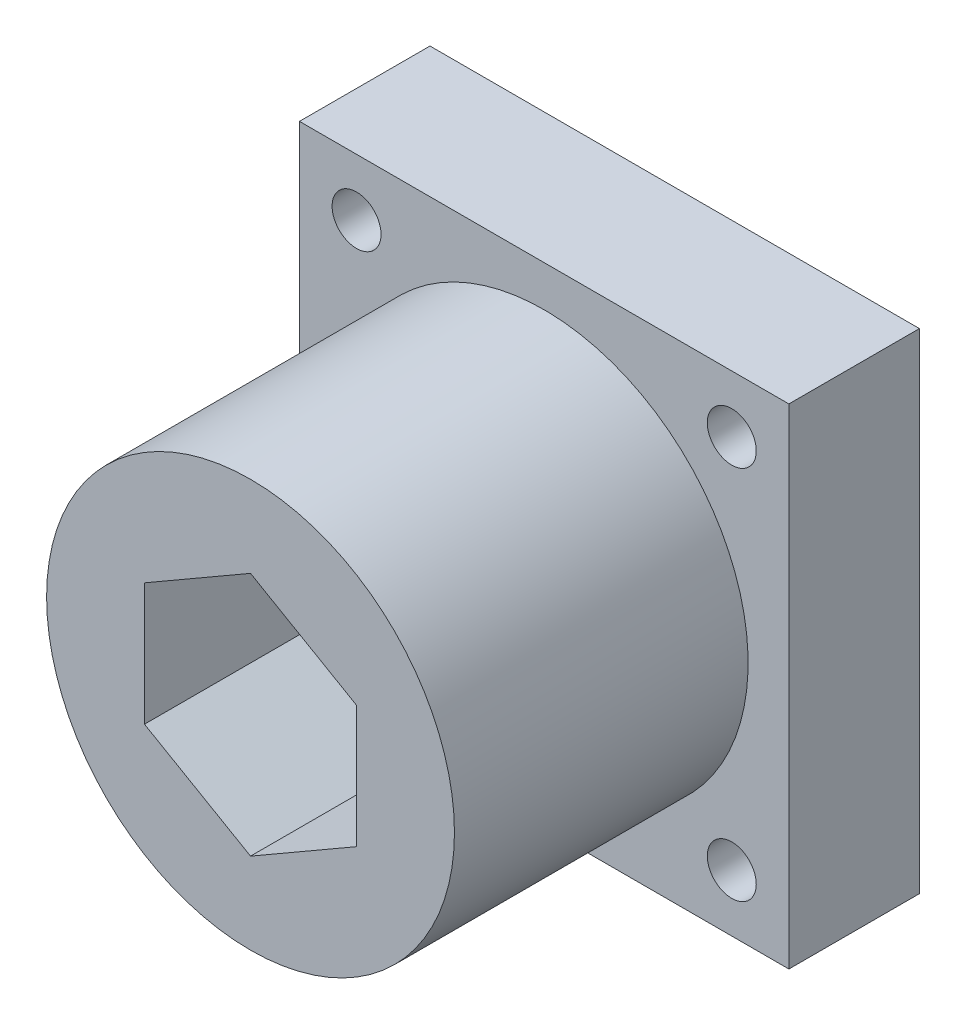
SolidWorks part; units mm, degrees
ref_plane "Ön Düzlem" through (0, 0, 0) normal (0, 0, 1) x (1, 0, 0)
ref_plane "Üst Düzlem" through (0, 0, 0) normal (0, 1, 0) x (1, 0, 0)
ref_plane "Sağ Düzlem" through (0, 0, 0) normal (1, 0, 0) x (0, 0, -1)
sketch "Çizim1" plane through (0, 0, 0) normal (0, 0, 1) x (1, 0, 0)
  line L1 (0, 0) -> (30, 0)
  line L2 (0, 0) -> (0, 30)
  line L3 (0, 30) -> (30, 30)
  line L4 (30, 0) -> (30, 30)
  dimension "D1" = 30
extrude "Yükseklik-Ekstrüzyon1" add sketch "Çizim1" along normal blind 8
sketch "Çizim2" plane through (0, 0, 8) normal (0, 0, 1) x (1, 0, 0)
  line L0 (30, 0) -> (30, 30) construction
  line L1 (0, 0) -> (30, 0) construction
  line L3 (15, 22.5056) -> (8.5, 18.7528)
  line L4 (8.5, 18.7528) -> (8.5, 11.2472)
  line L5 (8.5, 11.2472) -> (15, 7.4944)
  line L6 (15, 7.4944) -> (21.5, 11.2472)
  line L7 (21.5, 11.2472) -> (21.5, 18.7528)
  line L8 (21.5, 18.7528) -> (15, 22.5056)
  circle A0 centre (15, 15) radius 12.5
  circle A1 centre (15, 15) radius 6.5 construction
  dimension "D1" = 25
  dimension "D2" = 15
  dimension "D3" = 15
  dimension "D4" = 13
extrude "Yükseklik-Ekstrüzyon2" add sketch "Çizim2" along normal blind 8
sketch "Çizim3" plane through (0, 0, 8) normal (0, 0, 1) x (1, 0, 0)
  circle A0 centre (15, 15) radius 5.5
  circle A1 centre (15, 15) radius 12.5 construction
  dimension "D1" = 11
extrude "Kes-Ekstrüzyon1" cut sketch "Çizim3" against normal blind 8
sketch "Çizim4" plane through (0, 0, 8) normal (0, 0, 1) x (1, 0, 0)
  line L0 (30, 30) -> (0, 30) construction
  line L1 (0, 30) -> (0, 0) construction
  line L2 (30, 0) -> (30, 30) construction
  line L3 (0, 0) -> (30, 0) construction
  circle A0 centre (3.5, 26.5) radius 1.5
  circle A1 centre (26.5, 26.5) radius 1.5
  circle A2 centre (26.5, 3.5) radius 1.5
  circle A3 centre (3.5, 3.5) radius 1.5
  dimension "D1" = 3
  dimension "D2" = 3.5
  dimension "D3" = 3.5
  dimension "D4" = 3.5
  dimension "D5" = 3.5
  dimension "D6" = 3.5
  dimension "D7" = 3.5
  dimension "D8" = 3.5
  dimension "D9" = 3.5
extrude "Kes-Ekstrüzyon2" cut sketch "Çizim4" against normal blind 8
sketch "Çizim5" plane through (0, 0, 16) normal (0, 0, 1) x (1, 0, 0)
  line L0 (15, 22.5056) -> (8.5, 18.7528) construction
  line L1 (15, 22.5056) -> (8.5, 18.7528)
  line L2 (8.5, 18.7528) -> (8.5, 11.2472)
  line L3 (8.5, 11.2472) -> (15, 7.4944)
  line L4 (15, 7.4944) -> (21.5, 11.2472)
  line L5 (21.5, 11.2472) -> (21.5, 18.7528)
  line L6 (21.5, 18.7528) -> (15, 22.5056)
  line L7 (15, 22.5056) -> (8.5, 18.7528) construction
  circle A0 centre (15, 15) radius 12.5
  circle A1 centre (15, 15) radius 12.5 construction
  circle A2 centre (15, 15) radius 6.5 construction
extrude "Yükseklik-Ekstrüzyon3" add sketch "Çizim5" along normal blind 10
